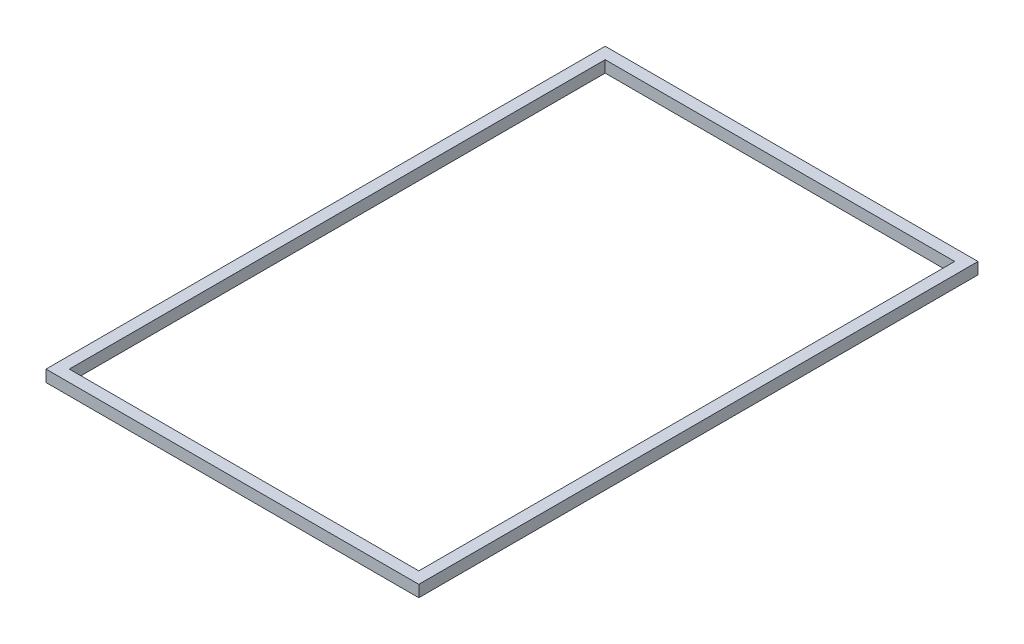
SolidWorks part; units mm, degrees
ref_plane "Front Plane" through (0, 0, 0) normal (0, 0, 1) x (1, 0, 0)
ref_plane "Top Plane" through (0, 0, 0) normal (0, 1, 0) x (1, 0, 0)
ref_plane "Right Plane" through (0, 0, 0) normal (1, 0, 0) x (0, 0, -1)
sketch "Sketch1" plane through (0, 0, 0) normal (0, 1, 0) x (1, 0, 0)
  line L1 (0, 0) -> (101.6, 0)
  line L2 (0, 0) -> (0, 152.4)
  line L3 (0, 152.4) -> (101.6, 152.4)
  line L4 (101.6, 0) -> (101.6, 152.4)
  line L5 (3.175, 3.175) -> (98.425, 3.175)
  line L6 (3.175, 3.175) -> (3.175, 149.225)
  line L7 (3.175, 149.225) -> (98.425, 149.225)
  line L8 (98.425, 3.175) -> (98.425, 149.225)
  dimension "D1" = 3.175
  dimension "D2" = 101.6
  dimension "D3" = 3.175
  dimension "D4" = 3.175
  dimension "D5" = 3.175
  dimension "D6" = 152.4
extrude "Boss-Extrude1" add sketch "Sketch1" along normal blind 3.175
